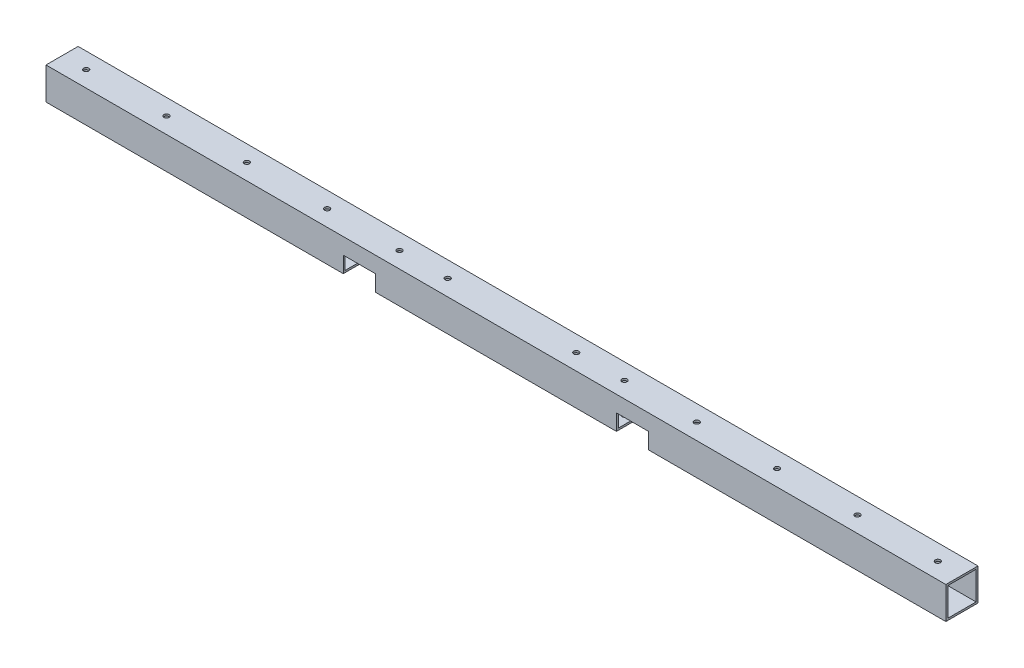
SolidWorks part; units mm, degrees
material "6061 合金"
ref_plane "前视基准面" through (0, 0, 0) normal (0, 0, 1) x (1, 0, 0)
ref_plane "上视基准面" through (0, 0, 0) normal (0, 1, 0) x (1, 0, 0)
ref_plane "右视基准面" through (0, 0, 0) normal (1, 0, 0) x (0, 0, -1)
sketch "草图1" plane through (0, 0, 0) normal (1, 0, 0) x (0, 0, -1)
  line L0 (-10, 10) -> (-10, -10)
  line L1 (-8.8, 8.8) -> (8.8, 8.8)
  line L2 (-8.8, 8.8) -> (-8.8, -8.8)
  line L3 (-8.8, -8.8) -> (8.8, -8.8)
  line L4 (8.8, 8.8) -> (8.8, -8.8)
  line L5 (-8.8, 8.8) -> (8.8, -8.8) construction
  line L6 (-8.8, -8.8) -> (8.8, 8.8) construction
  line L7 (-10, -10) -> (10, -10)
  line L8 (10, 10) -> (10, -10)
  line L9 (-10, 10) -> (10, 10)
  point P0 (0, 0)
  dimension "D1" = 1.2
  dimension "D2" = 20
  dimension "D3" = 20
extrude "凸台-拉伸2" add sketch "草图1" along normal mid plane 560
sketch "草图4" plane through (0, 0, 0) normal (0, 0, 1) x (1, 0, 0)
  line L0 (0, 112.156) -> (0, -69.1691) construction
  line L1 (280, -10) -> (-280, -10) construction
  line L2 (95, 0) -> (75, 0)
  line L3 (95, 0) -> (95, -10)
  line L4 (95, -10) -> (75, -10)
  line L5 (75, 0) -> (75, -10)
  line L6 (95, 0) -> (75, -10) construction
  line L7 (95, -10) -> (75, 0) construction
  line L8 (280, -10) -> (280, 10) construction
  line L9 (-95, -10) -> (-75, -10)
  line L10 (-75, 0) -> (-75, -10)
  line L11 (-95, 0) -> (-75, 0)
  line L12 (-95, 0) -> (-95, -10)
  point P3 (85, -5)
  dimension "D1" = 20
  dimension "D2" = 10
  dimension "D3" = 185
extrude "切除-拉伸2" cut sketch "草图4" against normal through all both and the other way through all
sketch "草图5" plane through (0, 10, 0) normal (0, 1, 0) x (1, 0, 0)
  line L0 (0, 292.1836) -> (0, -250.8863) construction
  line L1 (280, 0) -> (-280, 0) construction
  line L2 (280, 10) -> (280, -10) construction
  line L3 (-280, 10) -> (-280, -10) construction
  line L4 (95, 10) -> (75, 10) construction
  line L5 (95, 10) -> (75, 10) construction
  line L6 (85, 10) -> (85, -37.597) construction
  circle A1 centre (115, 0) radius 1.6
  circle A2 centre (165, 0) radius 1.6
  circle A3 centre (265, 0) radius 1.6
  circle A4 centre (215, 0) radius 1.6
  circle A5 centre (-215, 0) radius 1.6
  circle A6 centre (-265, 0) radius 1.6
  circle A7 centre (-165, 0) radius 1.6
  circle A8 centre (-115, 0) radius 1.6
  circle A10 centre (85, 0) radius 1.6 construction
  circle A11 centre (70, 0) radius 1.6
  circle A12 centre (-70, 0) radius 1.6
  circle A13 centre (-85, 0) radius 1.6 construction
  circle A14 centre (40, 0) radius 1.6
  circle A15 centre (-40, 0) radius 1.6
  dimension "D1" = 3.2
  dimension "D2" = 3.2
  dimension "D7" = 15
  dimension "D8" = 30
  dimension "D3" = 15
  dimension "D4" = 50
  dimension "D5" = 50
  dimension "D6" = 50
extrude "切除-拉伸3" cut sketch "草图5" against normal through all both and the other way through all
